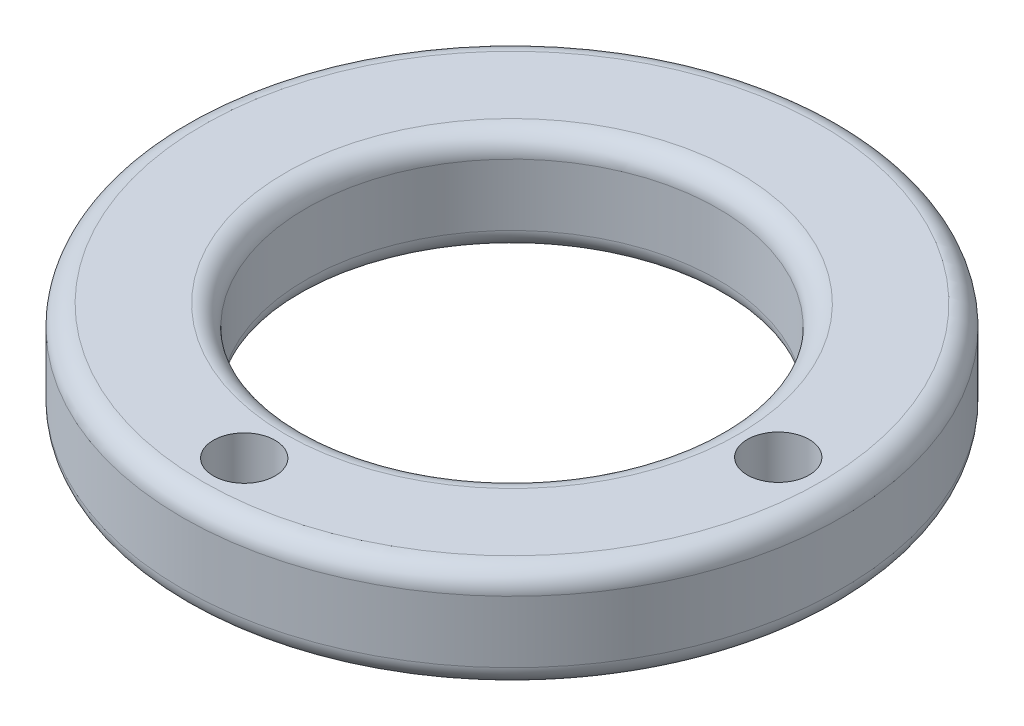
SolidWorks part; units mm, degrees
ref_plane "Front Plane" through (0, 0, 0) normal (0, 0, 1) x (1, 0, 0)
ref_plane "Top Plane" through (0, 0, 0) normal (0, 1, 0) x (1, 0, 0)
ref_plane "Right Plane" through (0, 0, 0) normal (1, 0, 0) x (0, 0, -1)
sketch "Sketch1" plane through (0, 0, 0) normal (0, 1, 0) x (1, 0, 0)
  circle A0 centre (0, 0) radius 16
  circle A1 centre (0, 0) radius 10
  circle A2 centre (0, -13) radius 1.5
  circle A3 centre (12.9258, 0) radius 1.5
  dimension "D1" = 20
  dimension "D2" = 6
  dimension "D3" = 3
  dimension "D5" = 3
  dimension "D4" = 13
extrude "Boss-Extrude1" add sketch "Sketch1" along normal blind 5
fillet "Fillet1" radius 1 4 edges at (0, 0, 10) (0, 0, 16) (0, 5, 16) (0, 5, 10)
